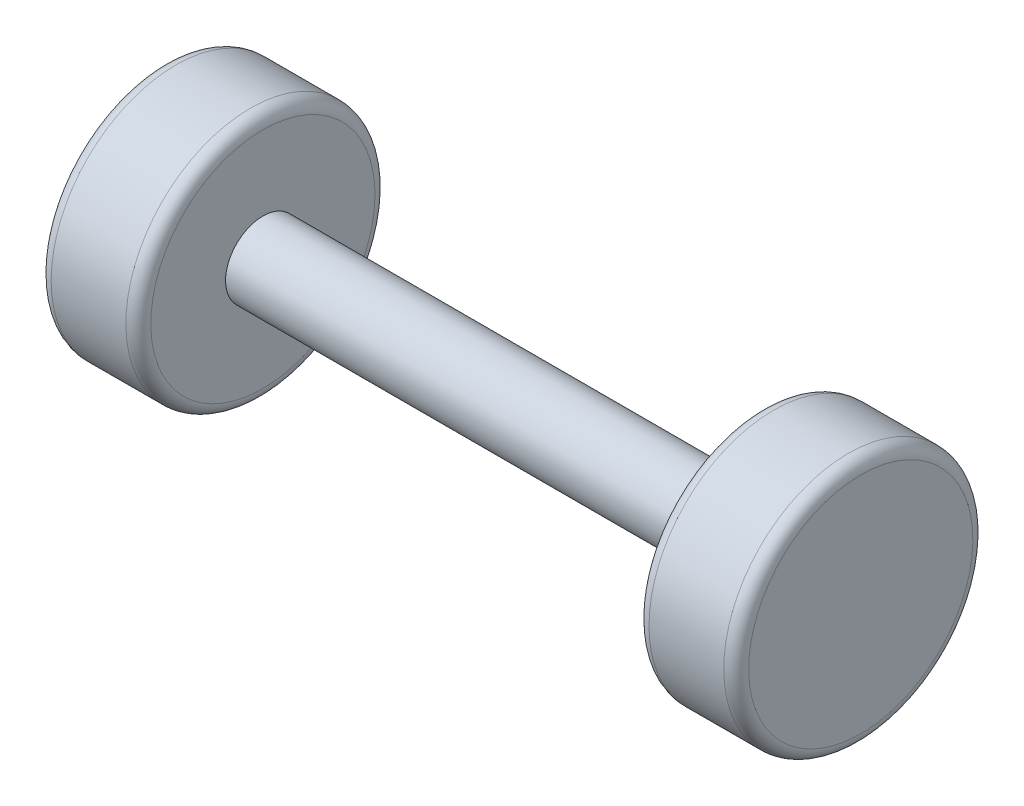
SolidWorks part; units mm, degrees
ref_plane "Plan de face" through (0, 0, 0) normal (0, 0, 1) x (1, 0, 0)
ref_plane "Plan de dessus" through (0, 0, 0) normal (0, 1, 0) x (1, 0, 0)
ref_plane "Plan de droite" through (0, 0, 0) normal (1, 0, 0) x (0, 0, -1)
sketch "Esquisse1" plane through (0, 0, 0) normal (0, 0, 1) x (1, 0, 0)
  line L1 (0, 0) -> (-140, 0)
  line L2 (0, 0) -> (0, 15)
  line L3 (0, 15) -> (-100, 15)
  line L5 (-140, 50) -> (-100, 50)
  line L6 (-140, 50) -> (-140, 0)
  line L8 (-100, 50) -> (-100, 15)
  point P6 (-84.7212, 0)
  point P9 (0, 0)
  dimension "D1" = 100
  dimension "D2" = 50
  dimension "D3" = 35
  dimension "D4" = 40
revolve "Révolution1" add sketch "Esquisse1" angle 360 about L1
mirror "Symétrie1" about plane through (0, 0, 0) normal (1, 0, 0) of "Révolution1"
fillet "Congé1" radius 5 4 edges at (-140, 50, 0) (-100, 50, 0) (100, 50, 0) (140, 50, 0)
